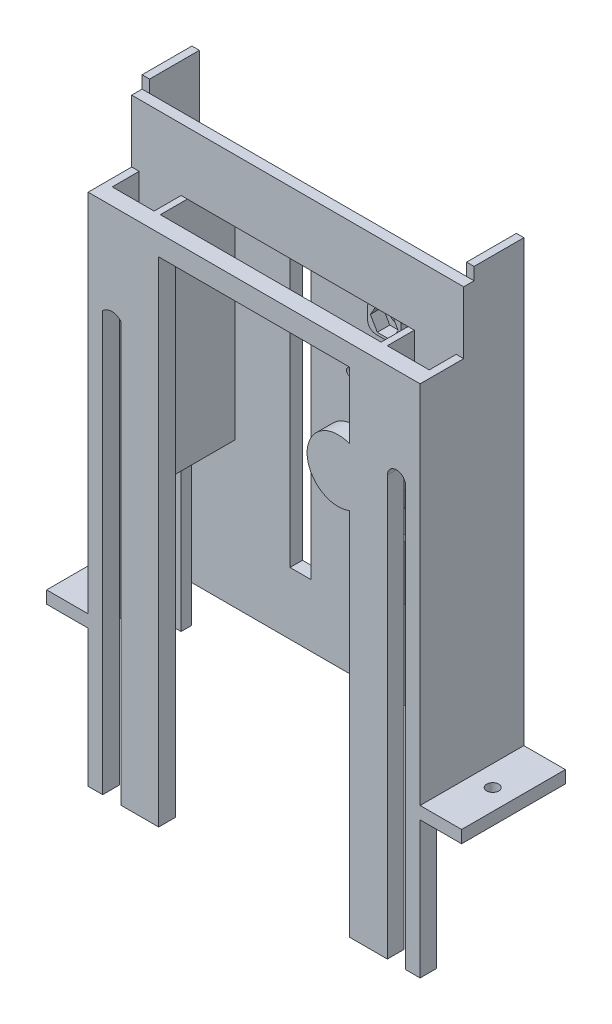
SolidWorks part; units mm, degrees
ref_plane "Front Plane" through (0, 0, 0) normal (0, 0, 1) x (1, 0, 0)
ref_plane "Top Plane" through (0, 0, 0) normal (0, 1, 0) x (1, 0, 0)
ref_plane "Right Plane" through (0, 0, 0) normal (1, 0, 0) x (0, 0, -1)
sketch "Sketch1" plane through (0, 0, 0) normal (0, 0, 1) x (1, 0, 0)
  line L0 (0, 87.3129) -> (0, -99.6485)
  line L1 (-40, 28) -> (40, 28)
  line L2 (-40, 28) -> (-40, -28)
  line L3 (-40, -28) -> (40, -28)
  line L4 (40, 28) -> (40, -28)
  line L5 (-40, 28) -> (40, -28) construction
  line L6 (-40, -28) -> (40, 28) construction
  line L7 (-23, 58.4535) -> (-23, -153.9501)
  line L8 (-36.5, -28) -> (-36.5, 23)
  line L13 (-36.5, 23) -> (-32.1, 23)
  line L14 (-32.1, 23) -> (-32.1, -28)
  line L15 (23, 58.4535) -> (23, -153.9501)
  line L16 (32.1, 23) -> (32.1, -28)
  line L17 (36.5, 23) -> (32.1, 23)
  line L18 (36.5, -28) -> (36.5, 23)
  line L19 (40, 28) -> (40, -28)
  line L20 (-34.3, 23) -> (34.3, 23)
  arc A0 (-36.5, 23) -> (-32.1, 23) centre (-34.3, 23) cw
  arc A1 (36.5, 23) -> (32.1, 23) centre (34.3, 23) ccw
  point P0 (0, 0)
  dimension "D1" = 17
  dimension "D2" = 80
  dimension "D3" = 56
  dimension "D4" = 4.4
  dimension "D5" = 5
  dimension "D6" = 3.5
extrude "Boss-Extrude1" add sketch "Sketch1" along normal blind 4 contours L8 A0 L20 L7 L1 L2 L3 | L20 L14 L3 L7 | L7 L20 L0 L1 | L20 L15 L3 L16 | L0 L20 L15 L1 | A1 L18 L3 L4 L1 L15 L20
sketch "Sketch2" plane through (0, 0, 0) normal (0, 0, -1) x (-1, 0, 0)
  line L0 (-38.2, 28) -> (-38.2, -28)
  line L1 (-28.1, 28) -> (-28.1, -28)
  line L2 (-26.6, 28) -> (-26.6, -28)
  line L3 (0, 45.2622) -> (0, -39.8517) construction
  line L4 (36.5, -28) -> (36.5, 23)
  line L5 (40, -28) -> (36.5, -28)
  line L6 (40, 28) -> (40, -28)
  line L7 (23, -28) -> (23, 23)
  line L8 (32.1, -28) -> (23, -28)
  line L9 (32.1, 23) -> (32.1, -28)
  line L10 (26.6, 28) -> (26.6, -28)
  line L11 (28.1, 28) -> (28.1, -28)
  line L12 (38.2, 28) -> (38.2, -28)
  line L14 (-32.1, 23) -> (-32.1, -28)
  line L15 (-32.1, -28) -> (-23, -28)
  line L16 (-23, -28) -> (-23, 23)
  line L17 (-23, 23) -> (23, 23)
  line L18 (23, 23) -> (23, -28)
  line L19 (23, -28) -> (32.1, -28)
  line L20 (32.1, -28) -> (32.1, 23)
  line L21 (36.5, 23) -> (36.5, -28)
  line L22 (36.5, -28) -> (40, -28)
  line L23 (40, -28) -> (40, 28)
  line L24 (40, 28) -> (-40, 28)
  line L25 (-40, 28) -> (-40, -28)
  line L26 (-40, -28) -> (-36.5, -28)
  line L27 (-36.5, -28) -> (-36.5, 23)
  line L28 (-32.1, 23) -> (-32.1, -28)
  line L29 (-32.1, -28) -> (-23, -28)
  line L30 (-23, -28) -> (-23, 23)
  line L31 (-23, 23) -> (23, 23)
  line L32 (23, 23) -> (23, -28)
  line L33 (23, -28) -> (32.1, -28)
  line L34 (32.1, -28) -> (32.1, 23)
  line L35 (36.5, 23) -> (36.5, -28)
  line L36 (36.5, -28) -> (40, -28)
  line L37 (40, -28) -> (40, 28)
  line L38 (40, 28) -> (-40, 28)
  line L39 (-40, 28) -> (-40, -28)
  line L40 (-40, -28) -> (-36.5, -28)
  line L41 (-36.5, -28) -> (-36.5, 23)
  arc A0 (32.1, 23) -> (36.5, 23) centre (34.3, 23) cw
  arc A2 (36.5, 23) -> (32.1, 23) centre (34.3, 23) ccw
  arc A3 (-32.1, 23) -> (-36.5, 23) centre (-34.3, 23) ccw
  arc A4 (36.5, 23) -> (32.1, 23) centre (34.3, 23) ccw
  arc A5 (-32.1, 23) -> (-36.5, 23) centre (-34.3, 23) ccw
  line M22 (-32.1, -28) -> (-23, -28)
  line M31 (40, -28) -> (40, 28)
  line M32 (40, 28) -> (-40, 28)
  line M33 (-40, 28) -> (-40, -28)
  line M34 (-40, -28) -> (-36.5, -28)
  dimension "D2" = 1.8
  dimension "D3" = 1.5
  dimension "D4" = 10.1
  dimension "D1" = 0
extrude "Boss-Extrude2" add sketch "Sketch2" along normal blind 5 contours L0 M32 M33 M34 | L2 L1 M32 M22 | L11 L10 L8 M32 | L12 L5 M32 M31
sketch "Sketch3" plane through (0, 0, -5) normal (0, 0, -1) x (-1, 0, 0)
  line L0 (-28.1, 28) -> (-28.1, -28) construction
  line L1 (-28.1, 15) -> (-26.6, 15)
  line L2 (-28.1, 15) -> (-28.1, -15)
  line L3 (-28.1, -15) -> (-26.6, -15)
  line L4 (-26.6, 15) -> (-26.6, -15)
  line L5 (-26.6, 28) -> (-26.6, -28) construction
  point P8 (-26.6, 0)
  dimension "D1" = 30
extrude "Cut-Extrude1" cut sketch "Sketch3" against normal up to surface (5 mm away) up to face at (0, -1.25, 0)
sketch "Sketch4" plane through (0, 28, 0) normal (0, 1, 0) x (1, 0, 0)
  line L0 (-40, 5) -> (-40, 21)
  line L1 (-40, 21) -> (40, 21)
  line L2 (40, 21) -> (40, 5)
  line L3 (38.2, 5) -> (38.2, 21)
  line L4 (28.1, 5) -> (28.1, 21)
  line L5 (26.6, 5) -> (26.6, 21)
  line L6 (-26.6, 5) -> (-26.6, 21)
  line L7 (-28.1, 5) -> (-28.1, 21)
  line L8 (-38.2, 5) -> (-38.2, 21)
  line L9 (-40, 18) -> (40, 18)
  line L10 (-40, 5) -> (-38.2, 5) construction
  line M5 (-38.2, 5) -> (-40, 5)
  line M9 (40, 5) -> (38.2, 5)
  line M13 (28.1, 5) -> (26.6, 5)
  line M17 (-26.6, 5) -> (-28.1, 5)
  dimension "D1" = 3
  dimension "D2" = 16
extrude "Boss-Extrude3" add sketch "Sketch4" against normal up to surface (56 mm away) contours L9 L0 L8 M5 | L9 L7 L6 M17 | L7 L9 L6 L1 | L8 L9 L7 L1 | L0 L9 L8 L1 | L6 L9 L5 L1 | L9 L5 L4 M13 | L5 L9 L4 L1 | L4 L9 L3 L1 | L3 L9 L2 L1 | L9 L3 L2 M9 up to face at (-27.45, -28, -0.25)
sketch "Sketch5" plane through (0, 0, -21) normal (0, 0, -1) x (-1, 0, 0)
  line L0 (-40, -28) -> (-40, 28) construction
  circle A0 centre (-12.36, 17.5) radius 1.75
  circle A1 centre (-12.36, -17.5) radius 1.75
  circle A2 centre (-20.26, 0) radius 4.75
  dimension "D1" = 3.5
  dimension "D2" = 3.5
  dimension "D3" = 9.5
  dimension "D4" = 19.74
  dimension "D5" = 27.64
  dimension "D6" = 17.5
  dimension "D7" = 17.5
extrude "Cut-Extrude2" cut sketch "Sketch5" against normal up to surface (3 mm away) up to face at (33.15, 0, -18)
sketch "Sketch6" plane through (0, 0, -18) normal (0, 0, 1) x (1, 0, 0)
  line L1 (14.0343, 14.6) -> (15.7086, 17.5)
  line L2 (15.7086, 17.5) -> (14.0343, 20.4)
  line L3 (14.0343, 20.4) -> (10.6857, 20.4)
  line L4 (10.6857, 20.4) -> (9.0114, 17.5)
  line L5 (9.0114, 17.5) -> (10.6857, 14.6)
  line L6 (10.6857, 14.6) -> (14.0343, 14.6)
  line L7 (14.0343, -20.4) -> (15.7086, -17.5)
  line L8 (15.7086, -17.5) -> (14.0343, -14.6)
  line L9 (14.0343, -14.6) -> (10.6857, -14.6)
  line L10 (10.6857, -14.6) -> (9.0114, -17.5)
  line L11 (9.0114, -17.5) -> (10.6857, -20.4)
  line L12 (10.6857, -20.4) -> (14.0343, -20.4)
  line L13 (8.36, 21) -> (16.36, 21)
  line L14 (8.36, 21) -> (8.36, 14)
  line L15 (8.36, 14) -> (16.36, 14)
  line L16 (16.36, 21) -> (16.36, 14)
  line L17 (8.36, 21) -> (16.36, 14) construction
  line L18 (8.36, 14) -> (16.36, 21) construction
  line L19 (8.36, -14) -> (16.36, -14)
  line L20 (8.36, -14) -> (8.36, -21)
  line L21 (8.36, -21) -> (16.36, -21)
  line L22 (16.36, -14) -> (16.36, -21)
  line L23 (8.36, -14) -> (16.36, -21) construction
  line L24 (8.36, -21) -> (16.36, -14) construction
  circle A0 centre (12.36, 17.5) radius 1.75 construction
  circle A1 centre (12.36, 17.5) radius 1.75
  circle A2 centre (12.36, -17.5) radius 1.75 construction
  circle A3 centre (12.36, -17.5) radius 1.75
  circle A4 centre (12.36, 17.5) radius 2.9 construction
  circle A5 centre (12.36, -17.5) radius 2.9 construction
  dimension "D1" = 5.8
  dimension "D2" = 7
  dimension "D3" = 8
  dimension "D4" = 5.8
  dimension "D5" = 8
  dimension "D6" = 7
extrude "Boss-Extrude4" add sketch "Sketch6" along normal blind 3 contours L16 L13 L14 L15 L6 L5 L4 L3 L2 L1 | L22 L19 L20 L21 L12 L11 L10 L9 L8 L7
fillet "Fillet1" radius 2 8 edges at (16.36, 14, -16.5) (8.36, 14, -16.5) (16.36, 21, -16.5) (8.36, 21, -16.5) (16.36, -14, -16.5) (8.36, -14, -16.5) (16.36, -21, -16.5) (8.36, -21, -16.5)
sketch "Sketch7" plane through (0, 0, -5) normal (0, 0, 1) x (1, 0, 0)
  line L4 (28.1, 15) -> (26.6, 15)
  line L5 (26.6, 15) -> (26.6, -15)
  line L6 (26.6, -15) -> (28.1, -15)
  line L7 (28.1, -15) -> (28.1, 15)
  line L8 (28.1, 15) -> (26.6, 15)
  line L9 (26.6, 15) -> (26.6, -15)
  line L10 (26.6, -15) -> (28.1, -15)
  line L11 (28.1, -15) -> (28.1, 15)
  dimension "D1" = 0
extrude "Cut-Extrude3" cut sketch "Sketch7" against normal blind 7
sketch "Sketch8" plane through (0, 0, -21) normal (0, 0, -1) x (-1, 0, 0)
  line L0 (-40, -28) -> (40, -28) construction
  line L1 (13.35, -28) -> (8.35, -28)
  line L2 (13.35, -28) -> (13.35, 22)
  line L3 (13.35, 22) -> (8.35, 22)
  line L4 (8.35, -28) -> (8.35, 22)
  line L5 (40, -28) -> (40, 28) construction
  arc A0 (8.35, 22) -> (13.35, 22) centre (10.85, 22) cw
  line M7 (-40, -28) -> (40, -28)
  dimension "D1" = 5
  dimension "D2" = 50
  dimension "D3" = 26.65
extrude "Cut-Extrude4" cut sketch "Sketch8" against normal up to surface (3 mm away) contours L4 L2 L3 M7 | A0 L3 up to face at (12.36, -17.5, -18)
sketch "Sketch11" plane through (0, 0, -21) normal (0, 0, -1) x (-1, 0, 0)
  line L0 (-40, -28) -> (8.35, -28) construction
  line L1 (-24, -28) -> (-17, -28)
  line L2 (-24, -28) -> (-24, -25)
  line L3 (-24, -25) -> (-17, -25)
  line L4 (-17, -28) -> (-17, -25)
  line L5 (13.35, -28) -> (40, -28) construction
  line L6 (24, -28) -> (17, -28)
  line L7 (24, -28) -> (24, -25)
  line L8 (24, -25) -> (17, -25)
  line L9 (17, -28) -> (17, -25)
  line L10 (-40, -28) -> (-40, 28) construction
  line L11 (40, -28) -> (40, 28) construction
  dimension "D1" = 7
  dimension "D2" = 7
  dimension "D3" = 3
  dimension "D4" = 3
  dimension "D5" = 16
  dimension "D6" = 16
extrude "Boss-Extrude5" add sketch "Sketch11" along normal blind 10
sketch "Sketch12" plane through (40, 0, 0) normal (1, 0, 0) x (0, 0, -1)
  line L1 (-4, -28) -> (21, -28)
  line L2 (-4, -28) -> (-4, -25)
  line L3 (-4, -25) -> (21, -25)
  line L4 (21, -28) -> (21, -25)
extrude "Boss-Extrude6" add sketch "Sketch12" along normal blind 10
sketch "Sketch13" plane through (-40, 0, 0) normal (-1, 0, 0) x (0, 0, 1)
  line L4 (-21, -28) -> (4, -28)
  line L5 (-21, -25) -> (-21, -28)
  line L6 (4, -25) -> (-21, -25)
  line L7 (4, -28) -> (4, -25)
  line L8 (-21, -28) -> (4, -28)
  line L9 (-21, -25) -> (-21, -28)
  line L10 (4, -25) -> (-21, -25)
  line L11 (4, -28) -> (4, -25)
  dimension "D1" = 0
extrude "Boss-Extrude7" add sketch "Sketch13" along normal blind 10
sketch "Sketch14" plane through (0, -25, 0) normal (0, 1, 0) x (1, 0, 0)
  line L0 (40, 21) -> (40, -4) construction
  line L1 (40, -4) -> (50, -4) construction
  line L2 (50, -4) -> (50, 21) construction
  line L3 (50, 21) -> (40, 21) construction
  line L4 (17, 21) -> (24, 21) construction
  line L5 (24, 21) -> (24, 31) construction
  line L6 (24, 31) -> (17, 31) construction
  line L7 (17, 31) -> (17, 21) construction
  line L8 (-40, -4) -> (-40, 21) construction
  line L9 (-40, 21) -> (-50, 21) construction
  line L10 (-50, 21) -> (-50, -4) construction
  line L11 (-50, -4) -> (-40, -4) construction
  line L12 (-24, 21) -> (-17, 21) construction
  line L13 (-17, 21) -> (-17, 31) construction
  line L14 (-17, 31) -> (-24, 31) construction
  line L15 (-24, 31) -> (-24, 21) construction
  line L16 (40, 21) -> (40, -4)
  line L17 (40, -4) -> (50, -4)
  line L18 (50, -4) -> (50, 21)
  line L19 (50, 21) -> (40, 21)
  line L20 (17, 21) -> (24, 21)
  line L21 (24, 21) -> (24, 31)
  line L22 (24, 31) -> (17, 31)
  line L23 (17, 31) -> (17, 21)
  line L24 (-40, -4) -> (-40, 21)
  line L25 (-40, 21) -> (-50, 21)
  line L26 (-50, 21) -> (-50, -4)
  line L27 (-50, -4) -> (-40, -4)
  line L28 (-24, 21) -> (-17, 21)
  line L29 (-17, 21) -> (-17, 31)
  line L30 (-17, 31) -> (-24, 31)
  line L31 (-24, 31) -> (-24, 21)
  circle A0 centre (-45, 8.5) radius 1.75
  circle A1 centre (-20.5, 26) radius 1.75
  circle A2 centre (20.5, 26) radius 1.75
  circle A3 centre (45, 8.5) radius 1.75
  point P20 (-40, 8.5)
  point P28 (-45, 21)
  point P31 (45, 21)
  point P33 (-17, 26)
  point P36 (-20.5, 31)
  point P38 (20.5, 31)
  dimension "D1" = 3.5
extrude "Cut-Extrude6" cut sketch "Sketch14" against normal blind 3 contours A2 | A3 | A1 | A0
sketch "Sketch15" plane through (0, 0, 4) normal (0, 0, 1) x (1, 0, 0)
  circle A0 centre (20.26, 0) radius 4.75 construction
  circle A1 centre (20.26, 0) radius 4.75
  circle A2 centre (20.26, 0) radius 7.5
  line M19 (23, 23) -> (23, -28)
  dimension "D1" = 15
extrude "Boss-Extrude8" add sketch "Sketch15" against normal blind 4 contours A2 A1 M19 | A1 M19 | A2 A1 M19 | A1 M19
sketch "Sketch17" plane through (0, 0, -21) normal (0, 0, -1) x (-1, 0, 0)
  line L0 (34.3, 23) -> (-34.3, 23) construction
  line L1 (-23, 58.4535) -> (-23, -153.9501) construction
  line L2 (32.1, 23) -> (32.1, -28) construction
  line L3 (36.5, 23) -> (32.1, 23) construction
  line L4 (36.5, -28) -> (36.5, 23) construction
  line L5 (23, 58.4535) -> (23, -153.9501) construction
  line L6 (40, 28) -> (-40, 28) construction
  line L7 (40, 28) -> (40, -28) construction
  line L8 (40, -28) -> (-40, -28) construction
  line L9 (-40, 28) -> (-40, -28) construction
  line L10 (-40, 28) -> (-40, -28) construction
  line L11 (0, 87.3129) -> (0, -99.6485) construction
  line L12 (-36.5, -28) -> (-36.5, 23) construction
  line L13 (-36.5, 23) -> (-32.1, 23) construction
  line L14 (-32.1, 23) -> (-32.1, -28) construction
  line L15 (34.3, 23) -> (-34.3, 23)
  line L16 (-23, 58.4535) -> (-23, -153.9501)
  line L17 (32.1, 23) -> (32.1, -28)
  line L18 (36.5, 23) -> (32.1, 23)
  line L19 (36.5, -28) -> (36.5, 23)
  line L20 (23, 58.4535) -> (23, -153.9501)
  line L21 (40, 28) -> (-40, 28)
  line L22 (40, 28) -> (40, -28)
  line L23 (40, -28) -> (-40, -28)
  line L24 (-40, 28) -> (-40, -28)
  line L25 (-40, 28) -> (-40, -28)
  line L26 (0, 87.3129) -> (0, -99.6485)
  line L27 (-36.5, -28) -> (-36.5, 23)
  line L28 (-36.5, 23) -> (-32.1, 23)
  line L29 (-32.1, 23) -> (-32.1, -28)
  line L30 (-36, -28) -> (-36, 23)
  line L31 (-32.6, 23) -> (-32.6, -28)
  line L32 (32.6, 23) -> (32.6, -28)
  line L33 (36, -28) -> (36, 23)
  line L34 (-36.5, -9.1991) -> (-32.1, -9.1991)
  line L35 (-32.1, -9.1991) -> (36.5, -9.1991)
  arc A0 (36.5, 23) -> (32.1, 23) centre (34.3, 23) ccw construction
  arc A1 (-32.1, 23) -> (-36.5, 23) centre (-34.3, 23) ccw construction
  arc A2 (36.5, 23) -> (32.1, 23) centre (34.3, 23) ccw
  arc A3 (-32.1, 23) -> (-36.5, 23) centre (-34.3, 23) ccw
  arc A4 (-32.6, 23) -> (-36, 23) centre (-34.3, 23) ccw
  arc A5 (36, 23) -> (32.6, 23) centre (34.3, 23) ccw
  line M13 (-50, -28) -> (-24, -28)
  dimension "D1" = 0.5
  dimension "D2" = 0.5
  dimension "D3" = 0.5
  dimension "D4" = 0.5
  dimension "D5" = 0.5
  dimension "D6" = 0.5
extrude "Cut-Extrude8" cut sketch "Sketch17" against normal blind 4 contours L31 L28 L30 M13 | L23 L33 L18 L15 L32
sketch "Sketch18" plane through (0, 0, -21) normal (0, 0, -1) x (-1, 0, 0)
  line L1 (-26.26, 6) -> (-3.26, 6)
  line L2 (-26.26, 6) -> (-26.26, -6)
  line L3 (-26.26, -6) -> (-3.26, -6)
  line L4 (-3.26, 6) -> (-3.26, -6)
  circle A0 centre (-20.26, 0) radius 4.75 construction
  dimension "D4" = 6
  dimension "D1" = 12
  dimension "D2" = 23
  dimension "D3" = 6
extrude "Cut-Extrude9" cut sketch "Sketch18" against normal blind 10
sketch "Sketch19" plane through (0, -28, 0) normal (0, -1, 0) x (1, 0, 0)
  line L0 (-24, -21) -> (-50, -21) construction
  line L1 (-50, 4) -> (-38.2, 4)
  line L2 (-50, 4) -> (-50, -21)
  line L3 (-50, -21) -> (-38.2, -21)
  line L4 (-38.2, 0) -> (-38.2, -18)
  line L5 (36.5, 4) -> (50, 4) construction
  line L6 (38.2, 4) -> (50, 4)
  line L7 (38.2, 0) -> (38.2, -18)
  line L8 (38.2, -21) -> (50, -21)
  line L9 (50, 4) -> (50, -21)
  line L10 (-24, -21) -> (-38.2, -21)
  line L11 (38.2, 4) -> (-38.2, 4)
  line L13 (38.2, 0) -> (-38.2, 0)
  line L15 (38.2, -21) -> (24, -21)
  line L17 (38.2, -18) -> (-38.2, -18)
  line L20 (17, -21) -> (17, -31)
  line L21 (17, -31) -> (24, -31)
  line L22 (24, -21) -> (24, -31)
  line L24 (-24, -21) -> (-24, -31)
  line L25 (-24, -31) -> (-17, -31)
  line L26 (-17, -21) -> (-17, -31)
  line L27 (17, -21) -> (-17, -21)
  dimension "D1" = 11.8
  dimension "D2" = 11.8
  dimension "D3" = 4
  dimension "D4" = 3
  dimension "D5" = 11.8
  dimension "D6" = 11.8
extrude "Boss-Extrude10" add sketch "Sketch19" along normal blind 35
sketch "Sketch21" plane through (0, -63, 0) normal (0, -1, 0) x (1, 0, 0)
  circle A0 centre (45, -8.5) radius 1.45
  circle A1 centre (20.5, -26) radius 1.45
  circle A2 centre (-20.5, -26) radius 1.45
  circle A3 centre (-45, -8.5) radius 1.45
  dimension "D1" = 2.9
  dimension "D2" = 2.9
  dimension "D3" = 2.9
  dimension "D4" = 2.9
extrude "Cut-Extrude11" cut sketch "Sketch21" against normal through all
sketch "Sketch20" plane through (0, -25, 0) normal (0, 1, 0) x (1, 0, 0)
  line L1 (-50, 21) -> (-40, 21)
  line L2 (-50, 21) -> (-50, -4)
  line L3 (-50, -4) -> (-40, -4)
  line L4 (-40, 21) -> (-40, -4)
  line L5 (40, 21) -> (50, 21)
  line L6 (40, 21) -> (40, -4)
  line L7 (40, -4) -> (50, -4)
  line L8 (50, 21) -> (50, -4)
  line L9 (-24, 31) -> (-17, 31)
  line L10 (-24, 31) -> (-24, 21)
  line L11 (-24, 21) -> (-17, 21)
  line L12 (-17, 31) -> (-17, 21)
  line L13 (17, 31) -> (24, 31)
  line L14 (17, 31) -> (17, 21)
  line L15 (17, 21) -> (24, 21)
  line L16 (24, 31) -> (24, 21)
extrude "Cut-Extrude10" cut sketch "Sketch20" against normal blind 35
sketch "Sketch22" plane through (0, 0, 4) normal (0, 0, 1) x (1, 0, 0)
  line L0 (50, -63) -> (-50, -63) construction
  line L1 (-36.5, -28) -> (-32.1, -28)
  line L2 (-36.5, -28) -> (-36.5, -63)
  line L3 (-36.5, -63) -> (-32.1, -63)
  line L4 (-32.1, -28) -> (-32.1, -63)
  line L6 (32.1, -28) -> (36.5, -28)
  line L7 (32.1, -28) -> (32.1, -63)
  line L8 (32.1, -63) -> (36.5, -63)
  line L9 (36.5, -28) -> (36.5, -63)
extrude "Cut-Extrude12" cut sketch "Sketch22" against normal blind 10
sketch "Sketch23" plane through (0, 0, 4) normal (0, 0, 1) x (1, 0, 0)
  line L0 (32.1, -63) -> (-32.1, -63) construction
  line L1 (-23, -28) -> (23, -28)
  line L2 (-23, -28) -> (-23, -63)
  line L3 (-23, -63) -> (23, -63)
  line L4 (23, -28) -> (23, -63)
  line L5 (23, -6.9816) -> (23, -28) construction
  dimension "D1" = 0
extrude "Cut-Extrude13" cut sketch "Sketch23" against normal blind 10
sketch "Sketch25" plane through (0, 28, 0) normal (0, 1, 0) x (1, 0, 0)
  line L0 (38.2, 18) -> (38.2, 0) construction
  line L1 (40, 21) -> (38.2, 21)
  line L2 (40, 21) -> (40, 9)
  line L3 (40, 9) -> (38.2, 9)
  line L4 (38.2, 21) -> (38.2, 9)
  line L5 (-38.2, 18) -> (-38.2, 0) construction
  line L6 (-40, 21) -> (-38.2, 21)
  line L7 (-40, 21) -> (-40, 9)
  line L8 (-40, 9) -> (-38.2, 9)
  line L9 (-38.2, 21) -> (-38.2, 9)
  dimension "D1" = 12
  dimension "D2" = 12
extrude "Boss-Extrude12" add sketch "Sketch25" along normal blind 18
sketch "Sketch27" plane through (0, 0, -21) normal (0, 0, -1) x (-1, 0, 0)
  circle A0 centre (-1.26, 0) radius 1
  circle A1 centre (-28.56, 0) radius 1
extrude "Cut-Extrude15" cut sketch "Sketch27" against normal blind 5
sketch "Sketch28" plane through (0, -60, 0) normal (0, 1, 0) x (1, 0, 0)
  line L0 (-38.2, 21) -> (38.2, 21) construction
  line L1 (17, 31) -> (24, 31)
  line L2 (17, 31) -> (17, 21)
  line L3 (17, 21) -> (24, 21)
  line L4 (24, 31) -> (24, 21)
  line L5 (24, 21) -> (24, 31) construction
  line L18 (-24, 31) -> (-17, 31)
  line L19 (-24, 31) -> (-24, 21)
  line L20 (-24, 21) -> (-17, 21)
  line L21 (-17, 31) -> (-17, 21)
  line L26 (-24, 31) -> (-24, 21) construction
  line L27 (-17, 31) -> (-24, 31) construction
  dimension "D3" = 10
  dimension "D4" = 7
extrude "Cut-Extrude16" cut sketch "Sketch28" against normal through all contours L2 L1 L4 L3 | L18 L21 L20 L19
sketch "Sketch29" plane through (0, -63, 0) normal (0, 1, 0) x (1, 0, 0)
  line L0 (9.6, 31) -> (16.6, 31)
  line L1 (9.6, 31) -> (9.6, 21)
  line L2 (9.6, 21) -> (16.6, 21)
  line L3 (16.6, 31) -> (16.6, 21)
  line L4 (-16.6, 31) -> (-9.6, 31)
  line L5 (-16.6, 31) -> (-16.6, 21)
  line L6 (-16.6, 21) -> (-9.6, 21)
  line L7 (-9.6, 31) -> (-9.6, 21)
  line L8 (-38.2, 21) -> (38.2, 21) construction
  line L9 (-26.6, 18) -> (-26.6, 0) construction
  line L10 (26.6, 18) -> (26.6, 0) construction
  dimension "D1" = 10
  dimension "D2" = 10
  dimension "D3" = 7
  dimension "D4" = 7
  dimension "D5" = 0
  dimension "D6" = 0
  dimension "D7" = 10
  dimension "D8" = 10
extrude "Boss-Extrude13" add sketch "Sketch29" along normal blind 2
sketch "Sketch30" plane through (0, 28, 0) normal (0, 1, 0) x (1, 0, 0)
  line L0 (16.6, 31) -> (9.6, 31) construction
  line L1 (-9.6, 31) -> (-16.6, 31) construction
  line L2 (16.6, 21) -> (16.6, 31) construction
  line L3 (-9.6, 21) -> (-9.6, 31) construction
  circle A0 centre (13.1, 26.5) radius 1.5
  circle A1 centre (-13.1, 26.5) radius 1.5
  dimension "D1" = 3
  dimension "D2" = 3
  dimension "D5" = 3.5
  dimension "D6" = 3.5
  dimension "D3" = 4.5
  dimension "D4" = 4.5
extrude "Cut-Extrude17" cut sketch "Sketch30" against normal through all
sketch "Sketch31" plane through (0, 0, 4) normal (0, 0, 1) x (1, 0, 0)
sketch "Sketch32" plane through (0, 0, 4) normal (0, 0, 1) x (1, 0, 0)
  line L0 (-38, 26) -> (-30, 26)
  line L1 (-38, 26) -> (-38, 5)
  line L2 (-38, 5) -> (-36.5, 5)
  line L3 (-30, 26) -> (-30, 5)
  line L4 (-32.1, 5) -> (-30, 5)
  line L5 (-40, 28) -> (40, 28) construction
  line L6 (-40, 28) -> (-40, -60) construction
  line L7 (-36.5, -63) -> (-36.5, 23) construction
  line L8 (-32.1, 23) -> (-32.1, -63) construction
  arc A0 (-36.5, 5) -> (-32.1, 5) centre (-34.3, 2.9604) cw
  dimension "D3" = 3
  dimension "D1" = 21
  dimension "D2" = 8
  dimension "D4" = 2
  dimension "D5" = 2
extrude "Boss-Extrude14" add sketch "Sketch32" against normal up to surface (4 mm away) up to face at (27.35, -21.5, 0)
sketch "Sketch33" plane through (0, -63, 0) normal (0, -1, 0) x (1, 0, 0)
  line L1 (40, 0) -> (36.5, 0)
  line L2 (40, 0) -> (40, 4)
  line L3 (40, 4) -> (36.5, 4)
  line L4 (36.5, 0) -> (36.5, 4)
  line L5 (-40, 0) -> (-36.5, 0)
  line L6 (-40, 0) -> (-40, 4)
  line L7 (-40, 4) -> (-36.5, 4)
  line L8 (-36.5, 0) -> (-36.5, 4)
  line L9 (-32.1, 4) -> (-23, 4)
  line L10 (-32.1, 4) -> (-32.1, 0)
  line L11 (-32.1, 0) -> (-23, 0)
  line L12 (-23, 4) -> (-23, 0)
  line L13 (23, 4) -> (32.1, 4)
  line L14 (23, 4) -> (23, 0)
  line L15 (23, 0) -> (32.1, 0)
  line L16 (32.1, 4) -> (32.1, 0)
  dimension "D1" = 4
  dimension "D2" = 3.5
  dimension "D3" = 4
  dimension "D4" = 3.5
extrude "Boss-Extrude15" add sketch "Sketch33" along normal blind 33
sketch "Sketch34" plane through (0, 0, 4) normal (0, 0, 1) x (1, 0, 0)
  line L0 (40, 28) -> (40, -60) construction
  line L1 (30, 26) -> (38, 26)
  line L2 (30, 26) -> (30, 5)
  line L3 (30, 5) -> (32.1, 5)
  line L4 (38, 26) -> (38, 5)
  line L5 (-40, 28) -> (40, 28) construction
  line L6 (32.1, 23) -> (32.1, -96) construction
  line L7 (36.5, 5) -> (38, 5)
  arc A0 (32.1, 5) -> (36.5, 5) centre (34.3, 5) cw
  dimension "D6" = 2.2
  dimension "D1" = 8
  dimension "D2" = 2
  dimension "D3" = 2
  dimension "D4" = 21
  dimension "D5" = 2.2
extrude "Boss-Extrude16" add sketch "Sketch34" against normal up to surface (4 mm away) up to face at (27.35, -21.5, 0)
sketch "Sketch35" plane through (0, 0, -9) normal (0, 0, 1) x (1, 0, 0)
  line L1 (-40, 43) -> (40, 43)
  line L2 (-40, 43) -> (-40, 28)
  line L3 (-40, 28) -> (40, 28)
  line L4 (40, 43) -> (40, 28)
  dimension "D1" = 15
  dimension "D2" = 80
extrude "Boss-Extrude17" add sketch "Sketch35" along normal blind 2.5
sketch "Sketch36" plane through (0, 28, 0) normal (0, -1, 0) x (1, 0, 0)
  line L0 (-28.1, -18) -> (-28.1, 0) construction
  line L1 (-38.2, -6.5) -> (-28.1, -6.5)
  line L2 (-38.2, -6.5) -> (-38.2, -9)
  line L3 (-38.2, -9) -> (-28.1, -9)
  line L4 (-28.1, -6.5) -> (-28.1, -9)
  line L6 (28.1, -6.5) -> (38.2, -6.5)
  line L7 (28.1, -6.5) -> (28.1, -9)
  line L8 (28.1, -9) -> (38.2, -9)
  line L9 (38.2, -6.5) -> (38.2, -9)
extrude "Boss-Extrude18" add sketch "Sketch36" along normal up to surface (91 mm away) up to face at (11.6, -63, -26.5)
sketch "Sketch37" plane through (0, 0, -21) normal (0, 0, -1) x (-1, 0, 0)
  line L9 (13.35, -28) -> (8.35, -28)
  line L10 (13.35, -28) -> (13.35, -48)
  line L11 (13.35, -48) -> (8.35, -48)
  line L12 (8.35, -28) -> (8.35, -48)
  dimension "D1" = 5
  dimension "D2" = 20
extrude "Cut-Extrude18" cut sketch "Sketch37" against normal blind 5
